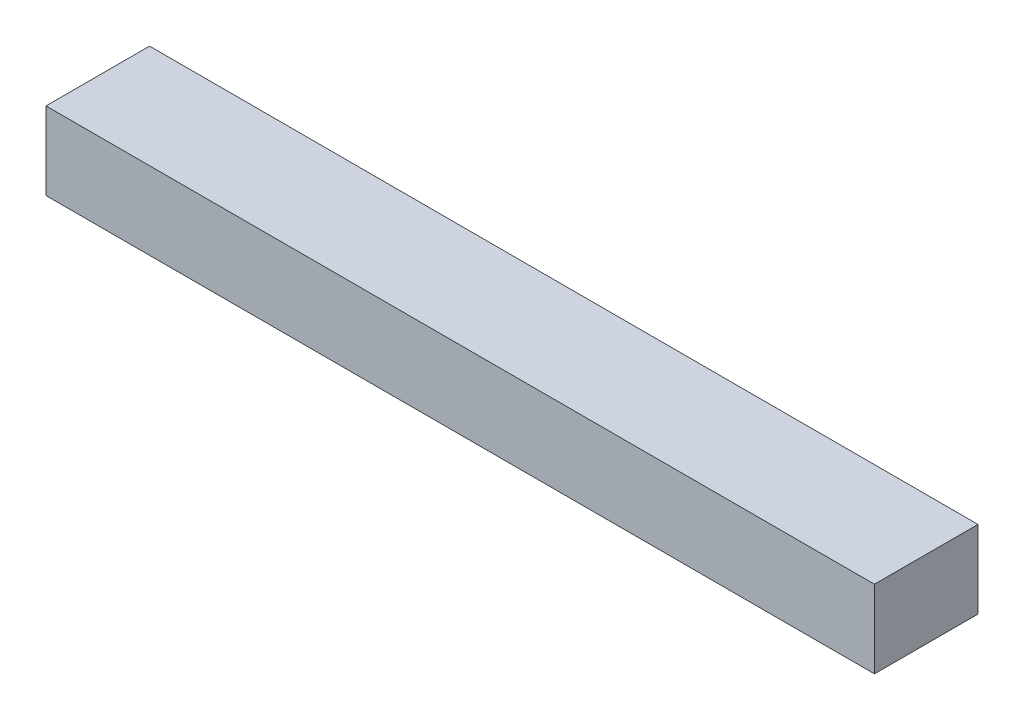
SolidWorks part; units mm, degrees
ref_plane "前视基准面" through (0, 0, 0) normal (0, 0, 1) x (1, 0, 0)
ref_plane "上视基准面" through (0, 0, 0) normal (0, 1, 0) x (1, 0, 0)
ref_plane "右视基准面" through (0, 0, 0) normal (1, 0, 0) x (0, 0, -1)
other "Configuration Table"
sketch "草图1" plane through (0, 0, 0) normal (0, 0, 1) x (1, 0, 0)
  line L1 (-64, -6) -> (64, -6)
  line L2 (-64, -6) -> (-64, 6)
  line L3 (-64, 6) -> (64, 6)
  line L4 (64, -6) -> (64, 6)
extrude "凸台-拉伸1" add sketch "草图1" against normal blind 16
